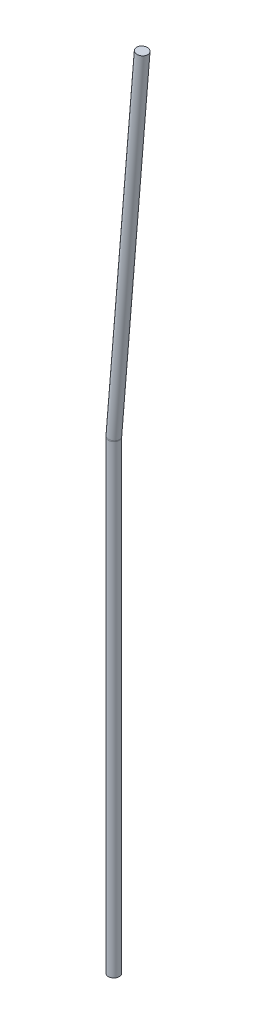
SolidWorks part; units mm, degrees
material "3.0517 (EN-AW 3003)"
ref_plane "Front" through (0, 0, 0) normal (0, 0, 1) x (1, 0, 0)
ref_plane "Top" through (0, 0, 0) normal (0, 1, 0) x (1, 0, 0)
ref_plane "Right" through (0, 0, 0) normal (1, 0, 0) x (0, 0, -1)
sketch "Sketch1" plane through (0, 0, 0) normal (0, 1, 0) x (1, 0, 0)
  circle A0 centre (0, 0) radius 0.2
  dimension "D1" = 0.4
extrude "Boss-Extrude1" add sketch "Sketch1" against normal blind 16.65
sketch "Sketch2" plane through (0, 0, 0) normal (0, 1, 0) x (1, 0, 0)
  line L0 (0.5, 0.2) -> (0.5, -0.2) construction
  circle A1 centre (0, 0) radius 0.2
  circle A2 centre (0, 0) radius 0.2
  point P5 (0.5, 0)
  dimension "D2" = 0.4
  dimension "D3" = 0.5
  dimension "D1" = 0
revolve "Revolve1" add sketch "Sketch2" angle 4.66 about L0
sketch "Sketch3" plane through (0.0033, 0.0405, 0) normal (0.0812, 0.9967, 0) x (0.9967, -0.0812, 0)
  circle A1 centre (-0.0017, 0) radius 0.2
  circle A2 centre (-0.0017, 0) radius 0.2
  dimension "D1" = 0
extrude "Boss-Extrude2" add sketch "Sketch3" along normal blind 12.5
